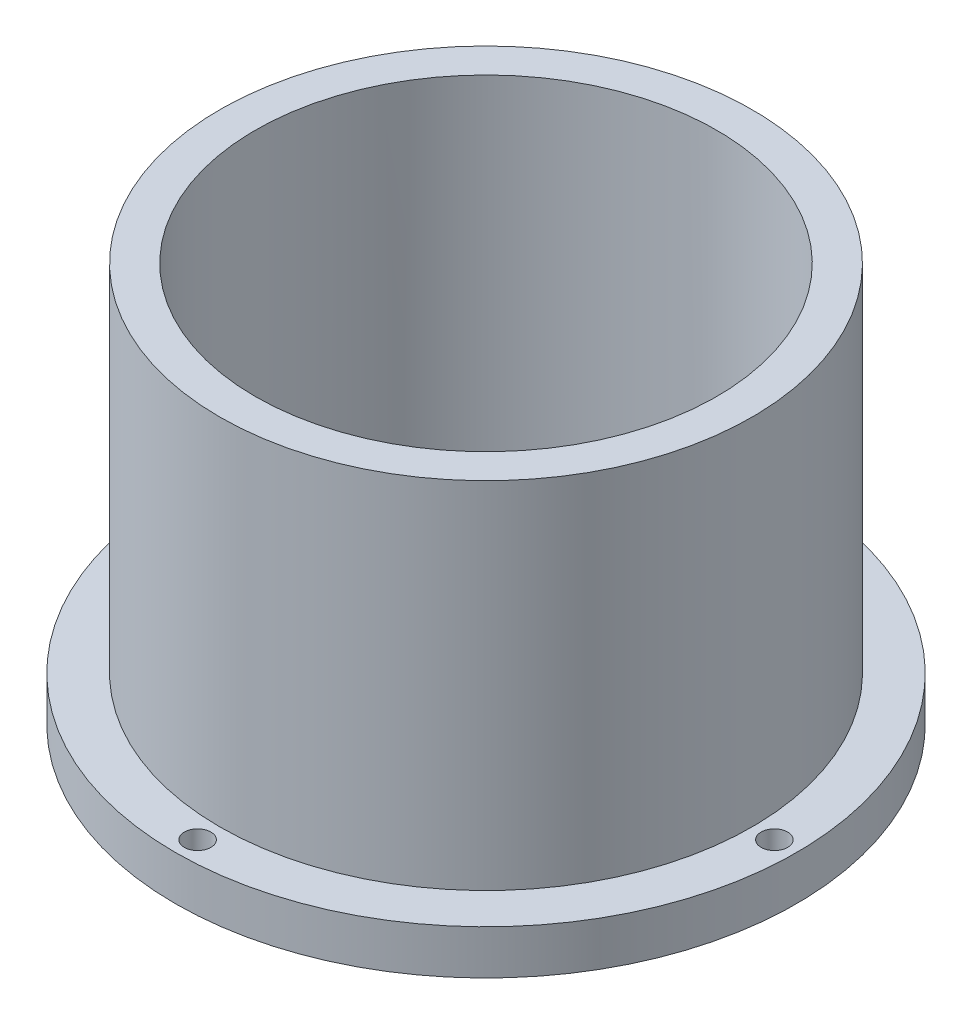
SolidWorks part; units mm, degrees
ref_plane "Front Plane" through (0, 0, 0) normal (0, 0, 1) x (1, 0, 0)
ref_plane "Top Plane" through (0, 0, 0) normal (0, 1, 0) x (1, 0, 0)
ref_plane "Right Plane" through (0, 0, 0) normal (1, 0, 0) x (0, 0, -1)
sketch "Sketch1" plane through (0, 0, 0) normal (0, 1, 0) x (1, 0, 0)
  circle A0 centre (0, 0) radius 35
  dimension "D1" = 70
extrude "Boss-Extrude1" add sketch "Sketch1" along normal blind 5
sketch "Sketch2" plane through (0, 5, 0) normal (0, 1, 0) x (1, 0, 0)
  circle A0 centre (0, 0) radius 30
  dimension "D1" = 60
extrude "Boss-Extrude2" add sketch "Sketch2" along normal blind 40
sketch "Sketch3" plane through (0, 45, 0) normal (0, 1, 0) x (1, 0, 0)
  circle A0 centre (0, 0) radius 26
  dimension "D1" = 52
extrude "Cut-Extrude2" cut sketch "Sketch3" against normal blind 60
sketch "Sketch4" plane through (0, 0, 0) normal (0, -1, 0) x (1, 0, 0)
  circle A0 centre (0, 0) radius 32.5 construction
  circle A1 centre (0, 32.5) radius 1.5
  circle A2 centre (32.5, 0) radius 1.5
  circle A3 centre (0, -32.5) radius 1.5
  circle A4 centre (-32.5, 0) radius 1.5
  dimension "D1" = 3
  dimension "D2" = 65
extrude "Cut-Extrude3" cut sketch "Sketch4" against normal blind 60
sketch "Sketch5" plane through (0, 0, 0) normal (0, -1, 0) x (1, 0, 0)
  circle A0 centre (0, 0) radius 26
extrude "Boss-Extrude3" add sketch "Sketch5" against normal blind 5
